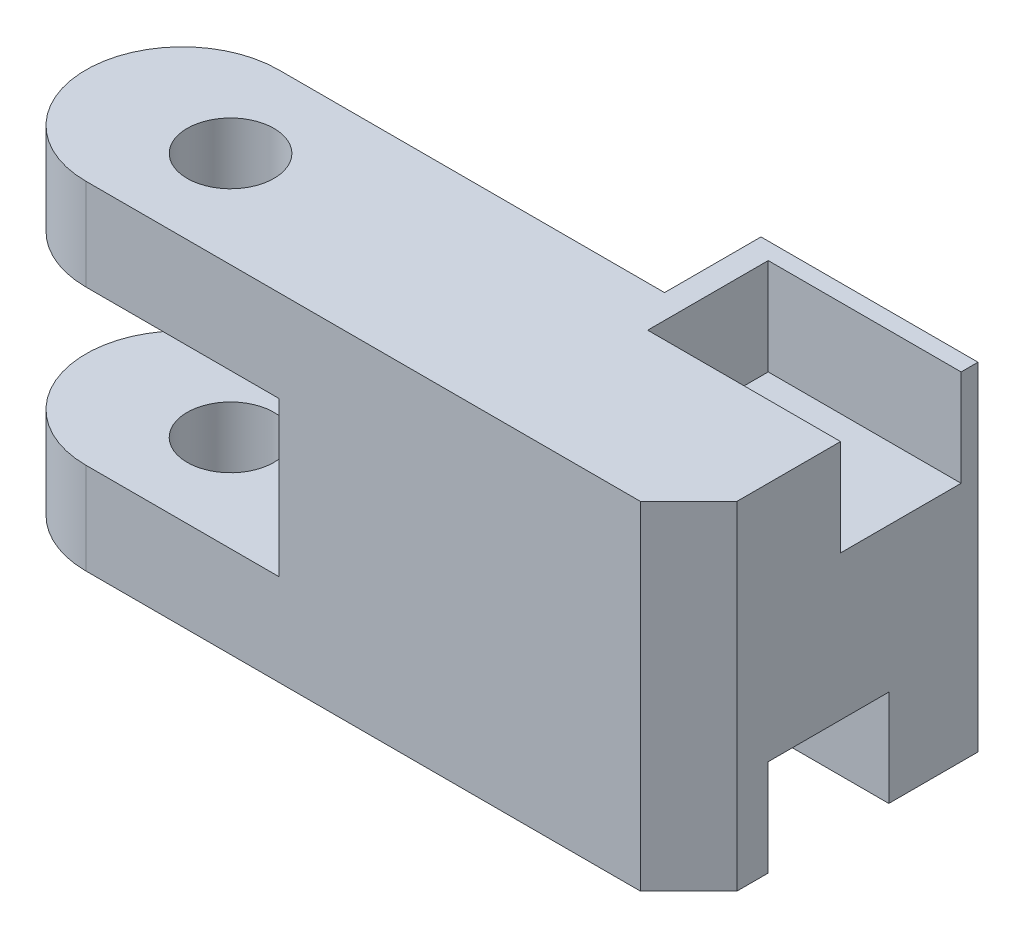
SolidWorks part; units mm, degrees
ref_plane "Front Plane" through (0, 0, 0) normal (0, 0, 1) x (1, 0, 0)
ref_plane "Top Plane" through (0, 0, 0) normal (0, 1, 0) x (1, 0, 0)
ref_plane "Right Plane" through (0, 0, 0) normal (1, 0, 0) x (0, 0, -1)
sketch "Sketch1" plane through (0, 0, 0) normal (0, 1, 0) x (1, 0, 0)
  line L1 (-1, 2) -> (7, 2)
  line L3 (-1, -2) -> (11.5, -2)
  line L4 (11.5, 2) -> (11.5, -2)
  line L5 (5.25, -2) -> (5.25, 2) construction
  line L6 (0, 0) -> (11.5, 0) construction
  line L7 (11.5, 2) -> (11.5, 4)
  line L8 (11.5, 4) -> (7, 4)
  line L9 (7, 4) -> (7, 2)
  circle A0 centre (0, 0) radius 0.9
  arc A2 (-1, 2) -> (-1, -2) centre (-1, 0) ccw
  point P10 (5.25, 2)
  point P12 (0, 0)
  point P315 (5.25, 0)
  dimension "D1" = 1.8
  dimension "D5" = 2
  dimension "D2" = 4
  dimension "D4" = 1
  dimension "D3" = 12.5
  dimension "D6" = 2
  dimension "D7" = 4.5
  dimension "D8" = 4
extrude "Boss-Extrude1" add sketch "Sketch1" along normal blind 7
sketch "Sketch2" plane through (0, 0, 2) normal (0, 0, 1) x (1, 0, 0)
  line L0 (-3, 3.5) -> (11.5, 3.5) construction
  line L1 (-3, 7) -> (-3, 0) construction
  line L2 (11.5, 7) -> (11.5, 0) construction
  line L4 (-3, 5.1) -> (3, 5.1)
  line L5 (-3, 5.1) -> (-3, 1.9)
  line L6 (-3, 1.9) -> (3, 1.9)
  line L7 (3, 5.1) -> (3, 1.9)
  line L8 (0, 1.9) -> (0, 5.1) construction
  line L9 (-3, 3.5) -> (3, 3.5) construction
  point P290 (0, 3.5)
  dimension "D1" = 3.2
  dimension "D2" = 6
extrude "Cut-Extrude1" cut sketch "Sketch2" against normal up to next
sketch "Sketch3" plane through (11.5, 0, 0) normal (1, 0, 0) x (0, 0, -1)
  line L0 (-2, 7) -> (-2, 0) construction
  line L1 (-2, 7) -> (4, 7) construction
  line L9 (1.15, 7) -> (1.15, 5)
  line L10 (1.15, 5) -> (3.65, 5)
  line L11 (3.65, 5) -> (3.65, 7)
  line L12 (3.65, 7) -> (1.15, 7)
  line L13 (-2, 0) -> (4, 0) construction
  line L14 (-0.35, 2) -> (2.15, 2)
  line L15 (-0.35, 2) -> (-0.35, 0)
  line L16 (-0.35, 0) -> (2.15, 0)
  line L17 (2.15, 2) -> (2.15, 0)
  line L18 (0.9, 0) -> (0.9, 2) construction
  line L19 (-0.35, 1) -> (2.15, 1) construction
  point P0 (-0.2654, 5)
  point P7 (0, 0)
  point P11 (-2, 3.5)
  point P15 (0, 0)
  point P24 (0, 0)
  point P26 (0, 0)
  point P27 (0, 0)
  point P28 (-1.6494, 3.5003)
  point P184 (0.9, 1)
  dimension "D1" = 2
  dimension "D2" = 2.5
  dimension "D3" = 2
  dimension "D4" = 1.5
  dimension "D5" = 2.5
  dimension "D6" = 1.65
extrude "Cut-Extrude2" cut sketch "Sketch3" against normal blind 4
sketch "Sketch4" [suppressed] plane through (0, 7, 0) normal (0, 1, 0) x (1, 0, 0)
  line L0 (11.5, 1.15) -> (11.1, -2)
  line L1 (-1, -2) -> (11.5, -2) construction
  line L2 (11.5, 1.15) -> (11.5, -2)
  line L3 (11.5, -2) -> (11.1, -2)
  dimension "D1" = 0.4
chamfer "Chamfer1" distance 1 angle 45 1 edges at (11.5, 3.5, 2)
equation "\"D3@Sketch1\"=\"D4@Sketch1\"+10-2.8+4+0.3"
